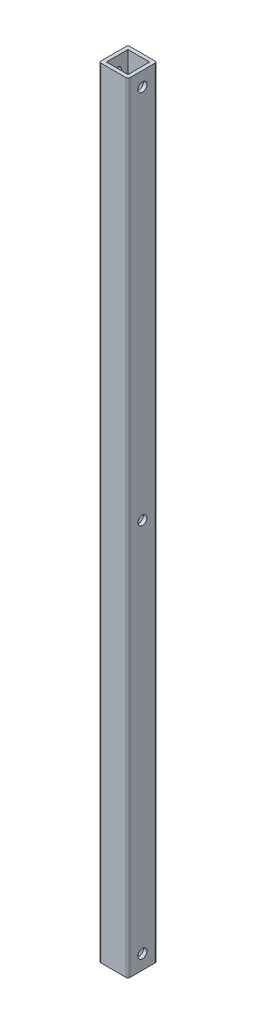
SolidWorks part; units mm, degrees
ref_plane "Front Plane" through (0, 0, 0) normal (0, 0, 1) x (1, 0, 0)
ref_plane "Top Plane" through (0, 0, 0) normal (0, 1, 0) x (1, 0, 0)
ref_plane "Right Plane" through (0, 0, 0) normal (1, 0, 0) x (0, 0, -1)
sketch "Sketch1" plane through (0, 0, 0) normal (0, 1, 0) x (1, 0, 0)
  line L0 (-3.5161, 3.7742) -> (-3.5161, -8.2258)
  line L1 (-5.5161, 5.7742) -> (10.4839, 5.7742)
  line L2 (-5.5161, 5.7742) -> (-5.5161, -10.2258)
  line L3 (-5.5161, -10.2258) -> (10.4839, -10.2258)
  line L4 (10.4839, 5.7742) -> (10.4839, -10.2258)
  line L5 (-3.5161, -8.2258) -> (8.4839, -8.2258)
  line L6 (8.4839, 3.7742) -> (8.4839, -8.2258)
  line L7 (-3.5161, 3.7742) -> (8.4839, 3.7742)
  dimension "D1" = 16
  dimension "D2" = 16
  dimension "D3" = 2
extrude "Boss-Extrude1" add sketch "Sketch1" along normal blind 432
fillet "Fillet1" radius 1 4 edges at (-5.5161, 216, -5.7742) (-5.5161, 216, 10.2258) (10.4839, 216, -5.7742) (10.4839, 216, 10.2258)
sketch "Sketch2" plane through (-5.5161, 0, 0) normal (-1, 0, 0) x (0, 0, 1)
  line L0 (-5.7742, 0) -> (-5.7742, 432) construction
  line L1 (-4.7742, 432) -> (9.2258, 432) construction
  line L2 (-4.7742, 0) -> (9.2258, 0) construction
  circle A0 centre (2.2258, 424) radius 2.5
  circle A1 centre (2.2258, 8) radius 2.5
  dimension "D3" = 5
  dimension "D4" = 5
  dimension "D1" = 8
  dimension "D2" = 8
  dimension "D5" = 8
  dimension "D6" = 8
extrude "Cut-Extrude1" cut sketch "Sketch2" against normal blind 16
sketch "Sketch3" plane through (-5.5161, 0, 0) normal (-1, 0, 0) x (0, 0, 1)
  line L0 (-5.7742, 0) -> (-5.7742, 432) construction
  line L1 (-4.7742, 432) -> (9.2258, 432) construction
  circle A0 centre (2.2258, 216) radius 2.5
  dimension "D1" = 5
  dimension "D2" = 8
  dimension "D3" = 216
extrude "Cut-Extrude2" cut sketch "Sketch3" against normal blind 16
